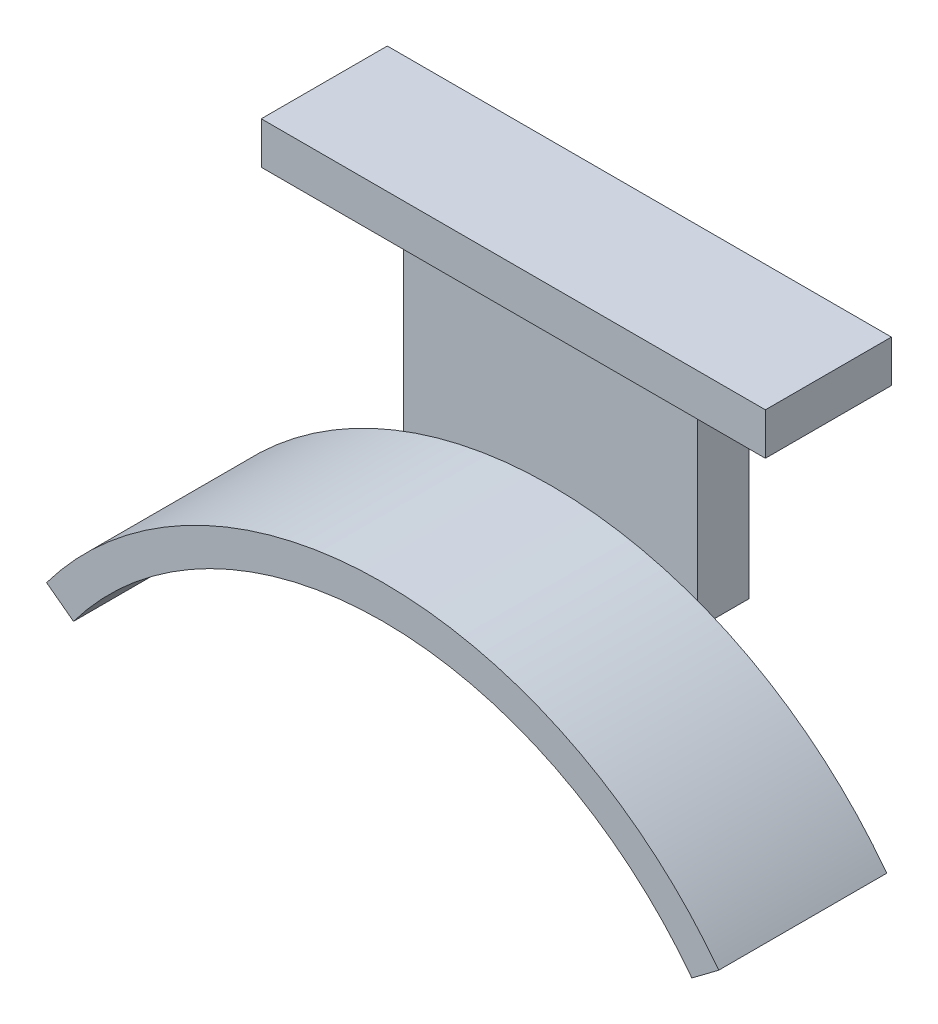
SolidWorks part; units mm, degrees
ref_plane "Front Plane" through (0, 0, 0) normal (0, 0, 1) x (1, 0, 0)
ref_plane "Top Plane" through (0, 0, 0) normal (0, 1, 0) x (1, 0, 0)
ref_plane "Right Plane" through (0, 0, 0) normal (1, 0, 0) x (0, 0, -1)
sketch "Sketch1" plane through (0, 0, 0) normal (0, 1, 0) x (1, 0, 0)
  line L1 (-38.1, 9.525) -> (38.1, 9.525)
  line L2 (-38.1, 9.525) -> (-38.1, -9.525)
  line L3 (-38.1, -9.525) -> (38.1, -9.525)
  line L4 (38.1, 9.525) -> (38.1, -9.525)
  line L5 (-38.1, 9.525) -> (38.1, -9.525) construction
  line L6 (-38.1, -9.525) -> (38.1, 9.525) construction
  point P0 (0, 0)
  dimension "D1" = 19.05
  dimension "D2" = 76.2
extrude "Boss-Extrude1" add sketch "Sketch1" along normal blind 6.35
sketch "Sketch2" plane through (0, 0, 0) normal (0, -1, 0) x (1, 0, 0)
  line L1 (-22.225, 3.891) -> (22.225, 3.891)
  line L2 (-22.225, 3.891) -> (-22.225, -3.891)
  line L3 (-22.225, -3.891) -> (22.225, -3.891)
  line L4 (22.225, 3.891) -> (22.225, -3.891)
  line L5 (-22.225, 3.891) -> (22.225, -3.891) construction
  line L6 (-22.225, -3.891) -> (22.225, 3.891) construction
  point P0 (0, 0)
  dimension "D1" = 44.45
extrude "Boss-Extrude2" add sketch "Sketch2" along normal blind 33.02
sketch "Sketch3" plane through (0, 0, 3.891) normal (0, 0, 1) x (1, 0, 0)
  line L0 (0, 0) -> (0, -25.4) construction
  line L4 (0, 0) -> (0, 28.3759) construction
  arc A1 (-50.7851, -50.8297) -> (50.8149, -50.7703) centre (0.0372, -88.9) cw
  point P0 (0, -25.4)
  point P5 (-38.0926, -35.7772)
  dimension "D1" = 101.6
  dimension "D2" = 63.5
  dimension "D3" = 25.4
extrude "Extrude-Thin1" add sketch "Sketch3" along normal blind 25.4 separate body thin
chamfer "Chamfer1" distance 3.81 angle 45 4 edges at (0, 0, -3.891) (-22.225, 0, 0) (0, 0, 3.891) (22.225, 0, 0)
